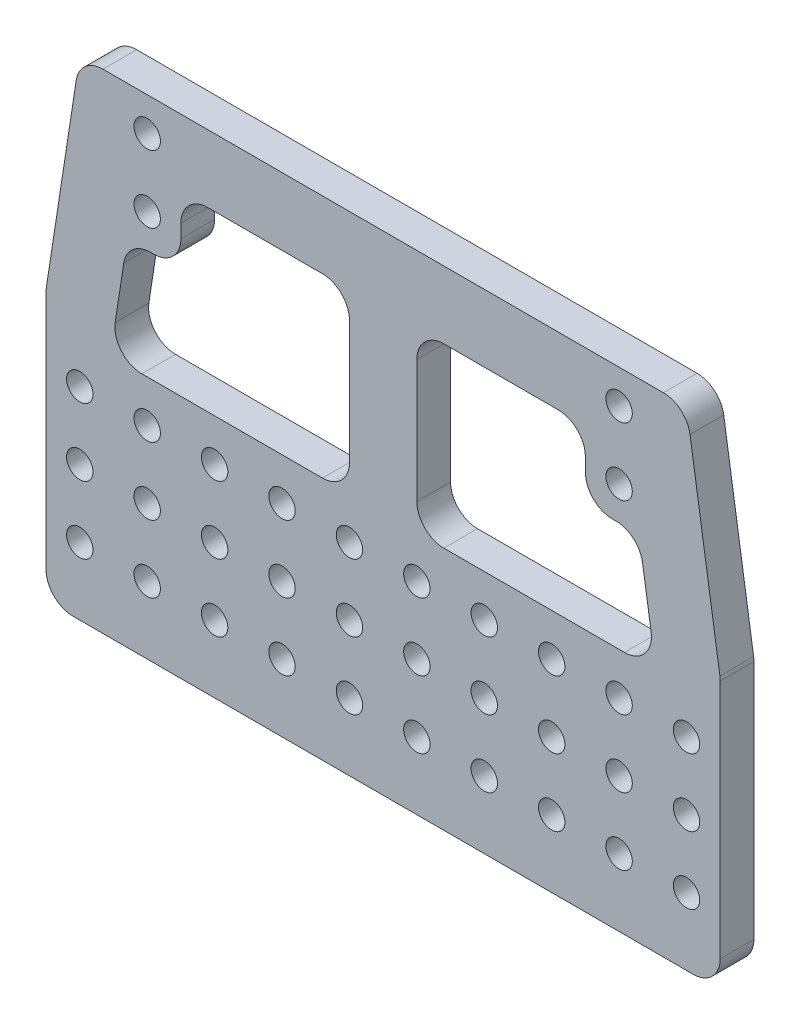
SolidWorks part; units mm, degrees
material "6061-T6 (SS)"
ref_plane "Front Plane" through (0, 0, 0) normal (0, 0, 1) x (1, 0, 0)
ref_plane "Top Plane" through (0, 0, 0) normal (0, 1, 0) x (1, 0, 0)
ref_plane "Right Plane" through (0, 0, 0) normal (1, 0, 0) x (0, 0, -1)
sketch "Sketch1" plane through (0, 0, 0) normal (0, 0, 1) x (1, 0, 0)
  line L1 (-57.15, 92.075) -> (57.15, 92.075)
  line L2 (57.15, 92.075) -> (63.5, 50.8)
  line L3 (63.5, 50.8) -> (63.5, 0)
  line L5 (-57.15, 92.075) -> (-63.5, 50.8)
  line L6 (-63.5, 50.8) -> (-63.5, 0)
  line L8 (-63.5, 0) -> (63.5, 0)
  line L10 (-44.45, 85.725) -> (44.45, 85.725) construction
  line L11 (-63.5, 25.4) -> (63.5, 25.4) construction
  circle A0 centre (44.45, 73.025) radius 2.4892
  circle A1 centre (44.45, 85.725) radius 2.4892
  circle A3 centre (-44.45, 73.025) radius 2.4892
  circle A4 centre (-44.45, 85.725) radius 2.4892
  circle A5 centre (6.35, 12.7) radius 2.4892
  circle A6 centre (6.35, 25.4) radius 2.4892
  circle A7 centre (6.35, 38.1) radius 2.4892
  circle A8 centre (19.05, 38.1) radius 2.4892
  circle A9 centre (19.05, 25.4) radius 2.4892
  circle A10 centre (19.05, 12.7) radius 2.4892
  circle A11 centre (31.75, 38.1) radius 2.4892
  circle A12 centre (31.75, 25.4) radius 2.4892
  circle A13 centre (31.75, 12.7) radius 2.4892
  circle A14 centre (44.45, 38.1) radius 2.4892
  circle A15 centre (44.45, 25.4) radius 2.4892
  circle A16 centre (44.45, 12.7) radius 2.4892
  circle A20 centre (-6.35, 12.7) radius 2.4892
  circle A21 centre (-6.35, 25.4) radius 2.4892
  circle A22 centre (-6.35, 38.1) radius 2.4892
  circle A23 centre (-19.05, 12.7) radius 2.4892
  circle A24 centre (-19.05, 25.4) radius 2.4892
  circle A25 centre (-19.05, 38.1) radius 2.4892
  circle A26 centre (-31.75, 12.7) radius 2.4892
  circle A27 centre (-31.75, 25.4) radius 2.4892
  circle A28 centre (-31.75, 38.1) radius 2.4892
  circle A29 centre (-44.45, 12.7) radius 2.4892
  circle A30 centre (-44.45, 25.4) radius 2.4892
  circle A31 centre (-44.45, 38.1) radius 2.4892
  circle A32 centre (57.15, 38.1) radius 2.4892
  circle A33 centre (57.15, 25.4) radius 2.4892
  circle A34 centre (57.15, 12.7) radius 2.4892
  circle A35 centre (-57.15, 12.7) radius 2.4892
  circle A36 centre (-57.15, 25.4) radius 2.4892
  circle A37 centre (-57.15, 38.1) radius 2.4892
  point P0 (0, 0)
  point P19 (0, 92.075)
  point P78 (0, 85.725)
  dimension "D8" = 12.7
  dimension "D9" = 12.7
  dimension "D6" = 4.9784
  dimension "D11" = 4.9784
  dimension "D2" = 88.9
  dimension "D3" = 12.7
  dimension "D4" = 50.8
  dimension "D5" = 6.35
  dimension "D7" = 19.05
  dimension "D10" = 12.7
  dimension "D13" = 12.7
  dimension "D14" = 12.7
  dimension "D15" = 47.625
  dimension "D17" = 6.35
  dimension "D12" = 5
  dimension "D16" = 6
extrude "Boss-Extrude1" add sketch "Sketch1" along normal mid plane 6.35
sketch "Sketch2" plane through (0, 0, 3.175) normal (0, 0, 1) x (1, 0, 0)
  line L0 (0, 0) -> (0, 92.075) construction
  line L1 (57.15, 92.075) -> (-57.15, 92.075) construction
  line L2 (-38.1, 79.375) -> (-6.35, 79.375)
  line L3 (38.1, 79.375) -> (38.1, 66.675)
  line L4 (38.1, 66.675) -> (48.2083, 66.675)
  line L5 (48.2083, 66.675) -> (51.3833, 46.0375)
  line L6 (51.3833, 46.0375) -> (6.35, 46.0375)
  line L8 (63.5, 50.8) -> (57.15, 92.075) construction
  line L9 (-48.2083, 66.675) -> (-51.3833, 46.0375)
  line L10 (-38.1, 66.675) -> (-48.2083, 66.675)
  line L11 (-38.1, 79.375) -> (-38.1, 66.675)
  line L12 (-6.35, 79.375) -> (-6.35, 46.0375)
  line L14 (6.35, 46.0375) -> (6.35, 79.375)
  line L15 (6.35, 79.375) -> (38.1, 79.375)
  line L16 (-6.35, 46.0375) -> (-51.3833, 46.0375)
  circle A0 centre (44.45, 73.025) radius 2.4892 construction
  point P16 (0, 46.0375)
  point P19 (0, 79.375)
  dimension "D1" = 12.7
  dimension "D2" = 6.35
  dimension "D3" = 6.35
  dimension "D4" = 12.7
  dimension "D5" = 6.35
  dimension "D6" = 6.35
extrude "Cut-Extrude1" cut sketch "Sketch2" against normal through all
fillet "Fillet1" radius 5.08 18 edges at (-57.15, 92.075, 0) (63.5, 50.8, 0) (63.5, 0, 0) (-63.5, 0, 0) (-63.5, 50.8, 0) (57.15, 92.075, 0) (48.2083, 66.675, 0) (51.3833, 46.0375, 0) (-48.2083, 66.675, 0) (-38.1, 66.675, 0) (-38.1, 79.375, 0) (38.1, 66.675, 0) (6.35, 79.375, 0) (38.1, 79.375, 0) (-51.3833, 46.0375, 0) (-6.35, 79.375, 0) (-6.35, 46.0375, 0) (6.35, 46.0375, 0)
